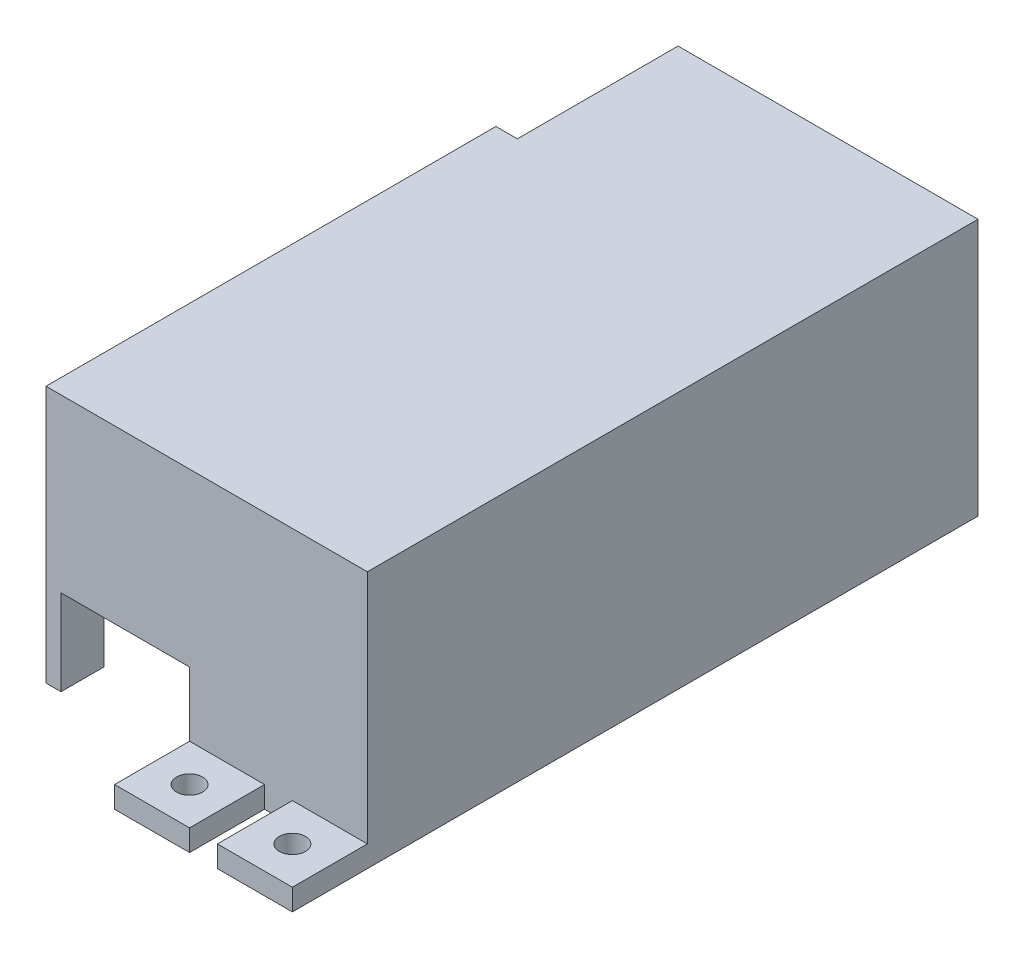
SolidWorks part; units mm, degrees
ref_plane "Front Plane" through (0, 0, 0) normal (0, 0, 1) x (1, 0, 0)
ref_plane "Top Plane" through (0, 0, 0) normal (0, 1, 0) x (1, 0, 0)
ref_plane "Right Plane" through (0, 0, 0) normal (1, 0, 0) x (0, 0, -1)
sketch "Sketch1" plane through (0, 0, 0) normal (0, 1, 0) x (1, 0, 0)
  line L1 (0, 0) -> (38.1, 0)
  line L2 (0, 0) -> (0, 53.34)
  line L3 (0, 53.34) -> (2.54, 53.34)
  line L4 (38.1, 0) -> (38.1, 53.34)
  line L6 (38.1, 53.34) -> (38.1, 72.39)
  line L7 (38.1, 72.39) -> (2.54, 72.39)
  line L8 (2.54, 53.34) -> (2.54, 72.39)
  dimension "D1" = 38.1
  dimension "D2" = 53.34
  dimension "D3" = 35.56
  dimension "D4" = 19.05
extrude "Boss-Extrude1" add sketch "Sketch1" along normal blind 30.48
shell "Shell1" thickness 1.778
sketch "Sketch7" plane through (0, 0, 0) normal (0, 0, 1) x (1, 0, 0)
  line L1 (1.778, 0) -> (17.018, 0)
  line L2 (1.778, 0) -> (1.778, 10.16)
  line L3 (1.778, 10.16) -> (17.018, 10.16)
  line L4 (17.018, 0) -> (17.018, 10.16)
  dimension "D1" = 15.24
  dimension "D2" = 10.16
extrude "Cut-Extrude3" cut sketch "Sketch7" against normal up to next
sketch "Sketch2" plane through (0, 0, 0) normal (0, 0, 1) x (1, 0, 0)
  line L0 (17.018, 0) -> (17.018, 10.16) construction
  line L1 (17.018, 0) -> (25.908, 0)
  line L2 (17.018, 0) -> (17.018, 2.54)
  line L3 (17.018, 2.54) -> (25.908, 2.54)
  line L4 (25.908, 0) -> (25.908, 2.54)
  line L5 (38.1, 0) -> (29.21, 0)
  line L6 (38.1, 0) -> (38.1, 2.54)
  line L7 (38.1, 2.54) -> (29.21, 2.54)
  line L8 (29.21, 0) -> (29.21, 2.54)
  line L9 (17.018, 0) -> (38.1, 0) construction
  dimension "D1" = 8.89
  dimension "D2" = 8.89
  dimension "D3" = 2.54
  dimension "D4" = 2.54
  dimension "D5" = 0
  dimension "D6" = 0
extrude "Boss-Extrude2" add sketch "Sketch2" along normal blind 8.89
sketch "Sketch3" plane through (0, 2.54, 0) normal (0, 1, 0) x (1, 0, 0)
  line L0 (25.908, -8.89) -> (17.018, -8.89) construction
  line L4 (17.018, -8.89) -> (17.018, 0) construction
  circle A0 centre (21.463, -4.445) radius 1.55
  dimension "D3" = 3.1
  dimension "D1" = 4.445
  dimension "D2" = 4.445
extrude "Cut-Extrude1" cut sketch "Sketch3" against normal through all
sketch "Sketch4" plane through (0, 2.54, 0) normal (0, 1, 0) x (1, 0, 0)
  line L0 (38.1, -8.89) -> (29.21, -8.89) construction
  line L1 (38.1, -8.89) -> (38.1, 0) construction
  circle A0 centre (33.655, -4.445) radius 1.55
  dimension "D3" = 3.1
  dimension "D1" = 4.445
  dimension "D2" = 4.445
extrude "Cut-Extrude2" cut sketch "Sketch4" against normal through all
sketch "Sketch8" plane through (0, 0, 0) normal (-1, 0, 0) x (0, 0, 1)
  line L0 (-53.34, 0) -> (0, 0) construction
  line L1 (-48.26, 22.86) -> (-5.08, 22.86)
  line L2 (-48.26, 22.86) -> (-48.26, 0)
  line L3 (-48.26, 0) -> (-5.08, 0)
  line L4 (-5.08, 22.86) -> (-5.08, 0)
  line L5 (-26.67, 0) -> (-26.67, 22.86) construction
  line L6 (-48.26, 11.43) -> (-5.08, 11.43) construction
  line L7 (-53.34, 30.48) -> (-53.34, 0) construction
  line L8 (0, 30.48) -> (0, 0) construction
  line L9 (-53.34, 30.48) -> (0, 30.48) construction
  point P648 (-26.67, 11.43)
  dimension "D1" = 5.08
  dimension "D2" = 5.08
  dimension "D3" = 7.62
extrude "Cut-Extrude4" cut sketch "Sketch8" against normal blind 11.684
